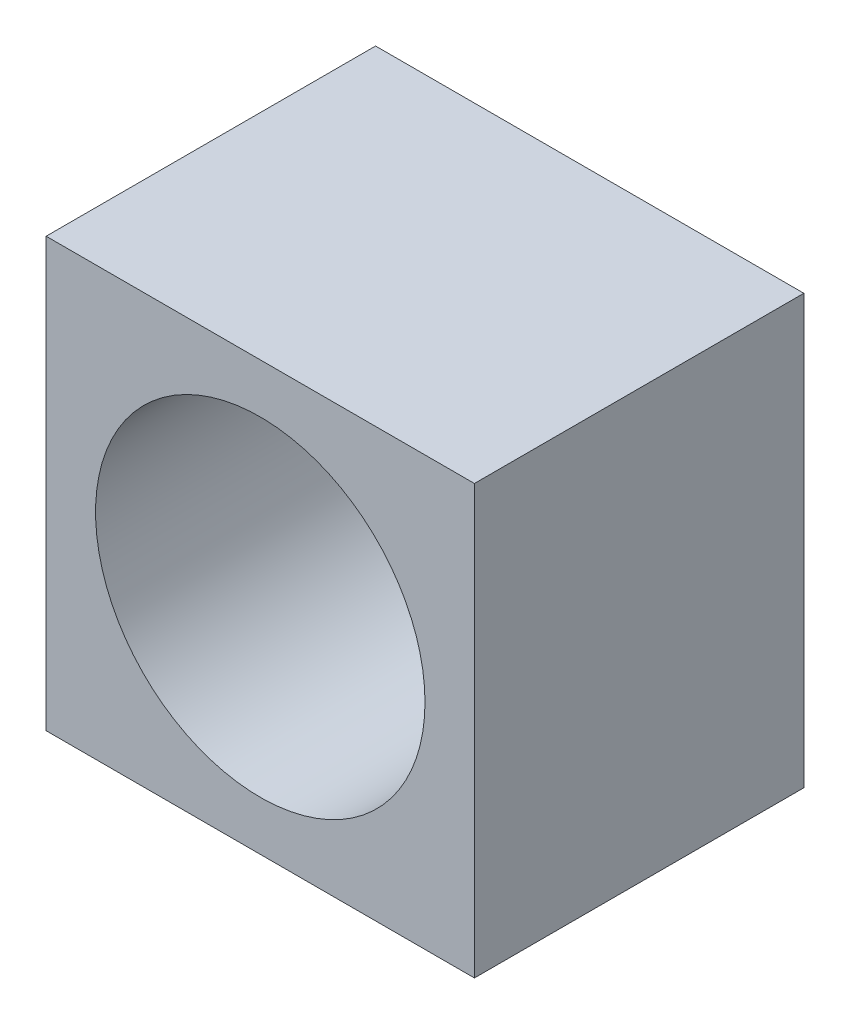
SolidWorks part; units mm, degrees
ref_plane "Piano frontale" through (0, 0, 0) normal (0, 0, 1) x (1, 0, 0)
ref_plane "Piano superiore" through (0, 0, 0) normal (0, 1, 0) x (1, 0, 0)
ref_plane "Piano destro" through (0, 0, 0) normal (1, 0, 0) x (0, 0, -1)
sketch "Schizzo13" plane through (0, 0, 0) normal (0, 0, 1) x (1, 0, 0)
  line L1 (-6.5, 6.5) -> (6.5, 6.5)
  line L2 (-6.5, 6.5) -> (-6.5, -6.5)
  line L3 (-6.5, -6.5) -> (6.5, -6.5)
  line L4 (6.5, 6.5) -> (6.5, -6.5)
  line L5 (-6.5, 6.5) -> (6.5, -6.5) construction
  line L6 (-6.5, -6.5) -> (6.5, 6.5) construction
  circle A0 centre (0, 0) radius 5
  dimension "13" = 10
  dimension "D2" = 13
  dimension "D3" = 13
extrude "Estrusione-Estrusione1" add sketch "Schizzo13" along normal blind 10
